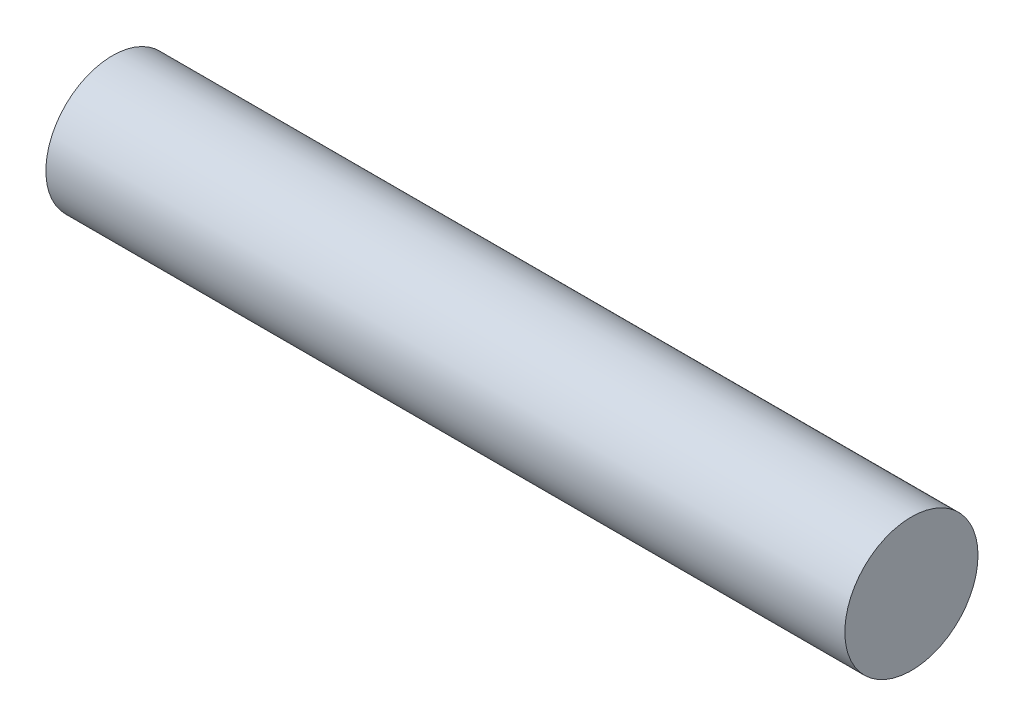
SolidWorks part; units mm, degrees
ref_plane "Front Plane" through (0, 0, 0) normal (0, 0, 1) x (1, 0, 0)
ref_plane "Top Plane" through (0, 0, 0) normal (0, 1, 0) x (1, 0, 0)
ref_plane "Right Plane" through (0, 0, 0) normal (1, 0, 0) x (0, 0, -1)
sketch "Sketch2" plane through (0, 0, 0) normal (0, 0, 1) x (1, 0, 0)
  line L0 (0, 0) -> (-113.9604, 0) construction
  line L1 (0, 0) -> (180, 0)
  line L2 (0, 0) -> (0, 15)
  line L3 (0, 15) -> (180, 15)
  line L4 (180, 0) -> (180, 15)
  dimension "D1" = 30
  dimension "D2" = 180
revolve "Revolve1" add sketch "Sketch2" angle 360 about L0
